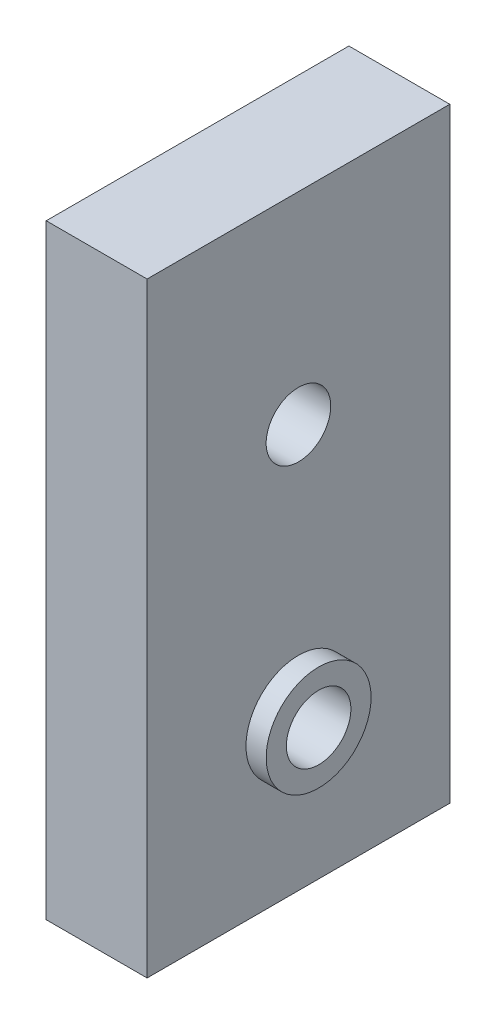
SolidWorks part; units mm, degrees
ref_plane "Front" through (0, 0, 0) normal (0, 0, 1) x (1, 0, 0)
ref_plane "Top" through (0, 0, 0) normal (0, 1, 0) x (1, 0, 0)
ref_plane "Right" through (0, 0, 0) normal (1, 0, 0) x (0, 0, -1)
sketch "Sketch1" plane through (0, 0, 0) normal (1, 0, 0) x (0, 0, -1)
  line L0 (7.5, 30) -> (7.5, 0)
  line L1 (0, 0) -> (15, 0)
  line L2 (0, 0) -> (0, 30)
  line L3 (0, 30) -> (15, 30)
  line L4 (15, 0) -> (15, 30)
  circle A0 centre (7.5, 7.5) radius 1.6
  circle A1 centre (7.5, 20) radius 1.6
  dimension "D3" = 7.5
  dimension "D1" = 30
  dimension "D2" = 15
  dimension "D4" = 20
extrude "Boss-Extrude1" add sketch "Sketch1" along normal blind 5 contours A1 L0 A0 L1 L4 L3 | A1 L0 L3 L2 L1 A0
sketch "Sketch2" plane through (5, 0, 0) normal (1, 0, 0) x (0, 0, -1)
  circle A0 centre (7.5, 7.5) radius 2.6
extrude "Extrude-Thin1" add sketch "Sketch2" along normal blind 1 thin thin type one direction reverse wall 1
